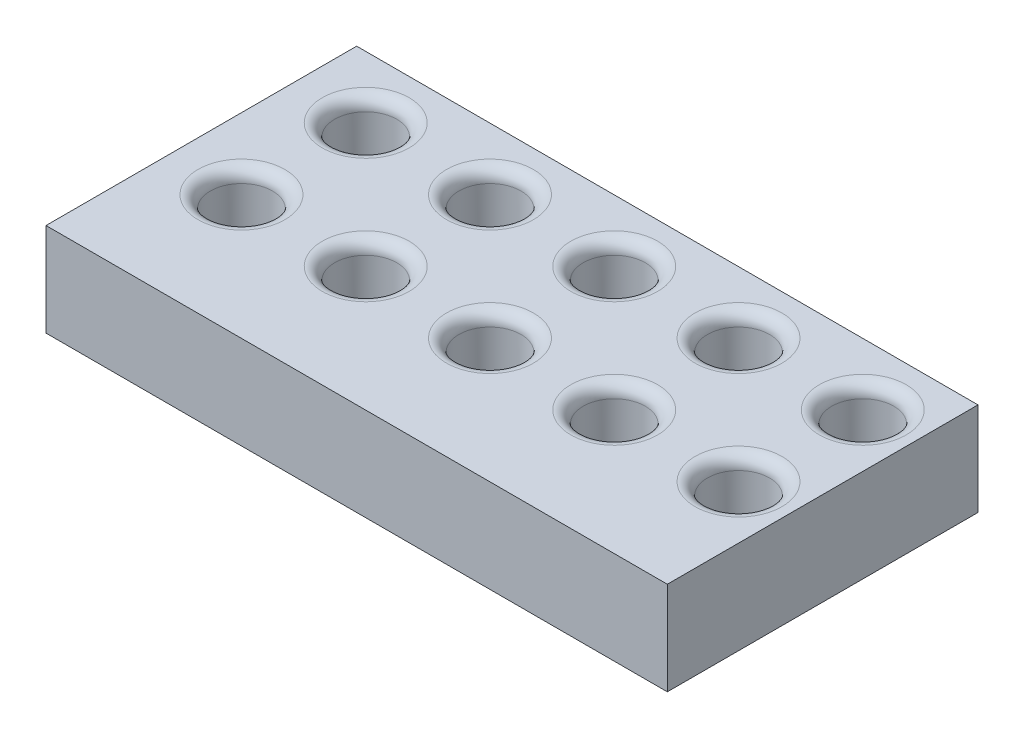
SolidWorks part; units mm, degrees
ref_plane "Front Plane" through (0, 0, 0) normal (0, 0, 1) x (1, 0, 0)
ref_plane "Top Plane" through (0, 0, 0) normal (0, 1, 0) x (1, 0, 0)
ref_plane "Right Plane" through (0, 0, 0) normal (1, 0, 0) x (0, 0, -1)
sketch "Sketch1" plane through (0, 0, 0) normal (0, 1, 0) x (1, 0, 0)
  line L1 (-50, -25) -> (50, -25)
  line L2 (-50, -25) -> (-50, 25)
  line L3 (-50, 25) -> (50, 25)
  line L4 (50, -25) -> (50, 25)
  line L5 (-50, -25) -> (50, 25) construction
  line L6 (-50, 25) -> (50, -25) construction
  point P0 (0, 0)
  dimension "D1" = 100
  dimension "D2" = 50
extrude "Boss-Extrude1" add sketch "Sketch1" along normal blind 15
sketch "Sketch2" plane through (0, 15, 0) normal (0, 1, 0) x (1, 0, 0)
  circle A0 centre (-38.5849, 15.0418) radius 5
  circle A1 centre (-18.5849, 15.0418) radius 5
  circle A2 centre (1.4151, 15.0418) radius 5
  circle A3 centre (21.4151, 15.0418) radius 5
  circle A4 centre (41.4151, 15.0418) radius 5
  circle A5 centre (-18.5849, -4.9582) radius 5
  circle A6 centre (1.4151, -4.9582) radius 5
  circle A7 centre (21.4151, -4.9582) radius 5
  circle A8 centre (41.4151, -4.9582) radius 5
  circle A9 centre (-38.5849, -4.9582) radius 5
  dimension "D1" = 10
  dimension "D2" = 5
  dimension "D3" = 2
extrude "Cut-Extrude1" cut sketch "Sketch2" against normal blind 10
fillet "Fillet2" radius 2 10 edges at (-38.5849, 15, 9.9582) (-18.5849, 15, 9.9582) (1.4151, 15, 9.9582) (21.4151, 15, 9.9582) (41.4151, 15, 9.9582) (41.4151, 15, -10.0418) (21.4151, 15, -10.0418) (1.4151, 15, -10.0418) (-18.5849, 15, -10.0418) (-38.5849, 15, -10.0418)
